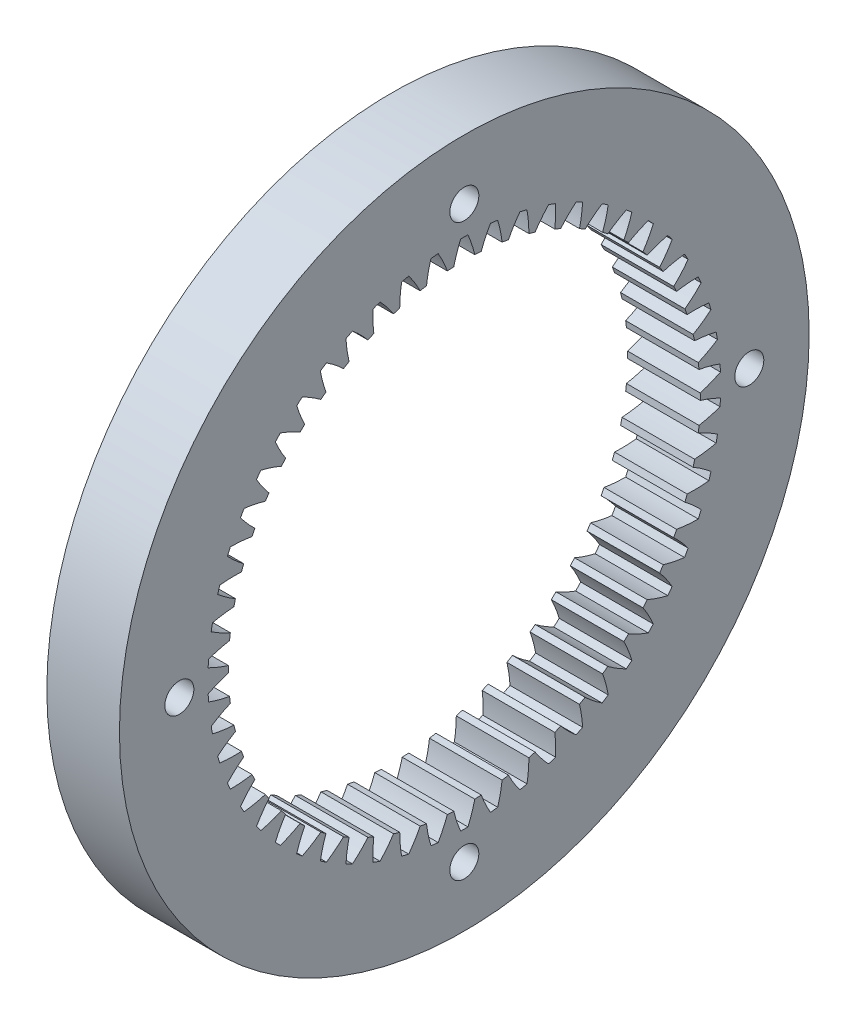
SolidWorks part; units mm, degrees
ref_plane "Plane1" through (0, 0, 0) normal (0, 0, 1) x (1, 0, 0)
ref_plane "Plane2" through (0, 0, 0) normal (0, 1, 0) x (1, 0, 0)
ref_plane "Plane3" through (0, 0, 0) normal (1, 0, 0) x (0, 0, -1)
sketch "HoldingSke" plane through (0, 0, 0) normal (0, 1, 0) x (1, 0, 0)
  line L0 (0, 0) -> (0.4702, -0.6472)
  line L1 (-15, 0) -> (100, 0) construction
  line L2 (0, 0) -> (-2.1039, 2.3779)
  line L3 (0, 0) -> (-11.863, 4.5341)
  line L4 (0, 0) -> (5.0761, 6.9867)
  line L5 (0, 0) -> (-23.7986, -8.8762)
  line L6 (0, 0) -> (-10.5278, -7.1032)
  line L7 (-2.1039, 2.3779) -> (3.3635, 27.1825)
  line L8 (-76.2, 3.6279) -> (-54.61, 3.6279)
  line L9 (-67.7845, 28.3722) -> (-49.3413, 33.142)
  line L10 (-76.2, 71.12) -> (104.1128, 71.12)
  line L11 (0, 0) -> (-10, 0)
  line L12 (-76.2, 101.6) -> (-76.155, 101.6)
  line L13 (24.9733, 27.94) -> (52.9518, 28.4284)
  line L14 (24.9733, 27.94) -> (24.9743, 27.94)
  line L15 (24.9733, 27.94) -> (100.4006, 29.5858)
  circle A0 centre (0, 0) radius 47.5
  circle A1 centre (0, 0) radius 12.7
  circle A2 centre (0, 0) radius 12.7
  dimension "MHD" = 25.4
  dimension "Hub_dia" = 25.4
  dimension "Diameter" = 95
  dimension "Num_teeth" = 54
  dimension "Pitch" = 0.8
  dimension "Overall_len" = 25.4
  dimension "Show_teeth" = 54
  dimension "Thickness" = 12.7
  dimension "OAL" = 25.4001
  dimension "T_dim" = 21.59
  dimension "Ap" = 14.5
  dimension "H" = 19.05
  dimension "Pitch_radius" = 180.3128
  dimension "Width" = 10
  dimension "Backlash" = 0.045
  dimension "Addendum_fac" = 1
  dimension "Dedendum_fac" = 1.25
  dimension "Clearance_fac" = 0.25
  dimension "Dedendum_add" = 0.001
  dimension "Module" = 1.25
sketch "BasProSke" plane through (0, 0, 0) normal (0, 1, 0) x (1, 0, 0)
  line L0 (-10, 0) -> (60, 0) construction
  line L1 (0, 32.5) -> (0, 47.5)
  line L2 (0, 32.5) -> (10, 32.5)
  line L3 (10, 32.5) -> (10, 47.5)
  line L4 (10, 47.5) -> (0, 47.5)
  dimension "Diameter" = 95
  dimension "Thickness" = 10
  dimension "Inside_diameter" = 65
revolve "Base-Revolve" add sketch "BasProSke" angle 360 about L0
sketch "TooCutSke" plane through (0, 0, 0) normal (1, 0, 0) x (0, 0, -1)
  line L3 (1.0941, 33.7323) -> (1.0941, 53.6633) construction
  line L4 (0, 0) -> (0, 59.563) construction
  line L5 (0, 0) -> (-3.9729, 68.2119) construction
  line L6 (-14.9767, 28.585) -> (36.0689, 31.5581) construction
  circle A0 centre (0, 0) radius 33.75 construction
  circle A1 centre (0, 0) radius 35.3135 construction
  circle A2 centre (0, 0) radius 29.4075 construction
  circle A3 centre (0, 0) radius 32.4746 construction
  arc A4 (1.4516, 32.4421) -> (0.5004, 35.31) centre (-14.9767, 28.585) ccw
  arc A5 (1.4516, 32.4421) -> (-1.4516, 32.4421) centre (0, 0) ccw
  arc A6 (0.5004, 35.31) -> (-0.5004, 35.31) centre (0, 0) ccw
  arc A7 (-0.5004, 35.31) -> (-1.4516, 32.4421) centre (14.9767, 28.585) ccw
  dimension "Pitch_dia" = 67.5
  dimension "Base_dia" = 58.815
  dimension "Root_dia" = 70.627
  dimension "Overcut_dia" = 64.9492
  dimension "Flank_rad" = 16.875
  dimension "Half_ang" = 3.333
  dimension "Half_CT" = 1.0941
extrude "ToothCut" cut sketch "TooCutSke" along normal through all
fillet "Breaks" [suppressed] radius 0.125
fillet "RootFillets" [suppressed] radius 0.3135
pattern_circular "TeethCuts" count 54 every 6.667 about axis through (-10, 0, 0) along (1, 0, 0) of "RootFillets", "Breaks", "ToothCut"
sketch "Sketch1" plane through (10, 0, 0) normal (1, 0, 0) x (0, 0, -1)
  circle A0 centre (0, 0) radius 39.25 construction
  circle A1 centre (0, 39.25) radius 2
  circle A2 centre (39.25, 0) radius 2
  circle A3 centre (0, -39.25) radius 2
  circle A4 centre (-39.25, 0) radius 2
  point P14 (0, 0)
  dimension "D1" = 78.5
  dimension "D2" = 4
  dimension "D3" = 4
extrude "Cut-Extrude1" cut sketch "Sketch1" against normal blind 10
equation "' \"Module@HoldingSke\" = 6.35"
equation "' \"Num_teeth@HoldingSke\" = 24"
equation "' \"Ap@HoldingSke\" =  14.5"
equation "' \"Ap@HoldingSke\" = 14.5"
equation "' \"Width@HoldingSke\" = 12"
equation "' \"Diameter@HoldingSke\" = 8 * 25.4"
equation "' \"Show_teeth@HoldingSke\" = 100"
equation "' \"Backlash@HoldingSke\" = 0.009 * 25.4"
equation "' \"Addendum_fac@HoldingSke\" = 1.0"
equation "' \"Dedendum_fac@HoldingSke\" = 1.25"
equation "' \"Dedendum_add@HoldingSke\" = 0.00005 * 25.4"
equation "' \"Clearance_fac@HoldingSke\" = 0.25"
equation "\"Pitch@HoldingSke\" = 1 / \"Module@HoldingSke\" "
equation "\"Overcut_dia@TooCutSke\" = (\"Num_teeth@HoldingSke\" - 2 * \"Addendum_fac@HoldingSke\") / \"Pitch@HoldingSke\" - 0.002 * 25.4"
equation "\"Pitch_dia@TooCutSke\" = \"Num_teeth@HoldingSke\" / \"Pitch@HoldingSke\""
equation "\"Base_dia@TooCutSke\" = \"Num_teeth@HoldingSke\" / \"Pitch@HoldingSke\" * cos((\"Ap@HoldingSke\"  * 3.14159265 / 180)) * 0.90"
equation "\"Root_dia@TooCutSke\" = \"Num_teeth@HoldingSke\"  / \"Pitch@HoldingSke\" + 2 *  \"Dedendum_fac@HoldingSke\"/ \"Pitch@HoldingSke\" + \"Dedendum_add@HoldingSke\" * 2"
equation "\"Half_ang@TooCutSke\" = 180 / \"Num_teeth@HoldingSke\""
equation "\"Half_CT@TooCutSke\" = \"Num_teeth@HoldingSke\" / \"Pitch@HoldingSke\" * sin((3.14159265 / 2 / \"Num_teeth@HoldingSke\")) / 2 + 10 * \"Backlash@HoldingSke\" / 4"
equation "\"Flank_rad@TooCutSke\" = \"Num_teeth@HoldingSke\" / \"Pitch@HoldingSke\" / 4"
equation "\"Radius@RootFillets\"= \"Clearance_fac@HoldingSke\" / \"Pitch@HoldingSke\" + \"Dedendum_add@HoldingSke\""
equation "\"Break_rad@Breaks\" = 0.02 / \"Pitch@HoldingSke\" * 5"
equation "\"Num_teeth@TeethCuts\" = int( \"Show_teeth@HoldingSke\" ) + 1"
equation "\"Num_teeth@TeethCuts\" = ((sgn( \"Num_teeth@TeethCuts\" - \"Num_teeth@HoldingSke\" )-1)*( \"Num_teeth@TeethCuts\" - \"Num_teeth@HoldingSke\" ))/-2+ \"Num_teeth@HoldingSke\""
equation "\"Num_teeth@TeethCuts\" = ((sgn( \"Num_teeth@TeethCuts\" - 2.0)+1)*( \"Num_teeth@TeethCuts\" - 2.0))/2 +2.0"
equation "\"Angle@TeethCuts\" = 360.0 / \"Num_teeth@HoldingSke\""
equation "\"Diameter@BasProSke\" = \"Num_teeth@HoldingSke\"  / \"Pitch@HoldingSke\" + 2 *  \"Dedendum_fac@HoldingSke\"/ \"Pitch@HoldingSke\" + \"Dedendum_add@HoldingSke\" * 2 + 0.002 * 25.4"
equation "\"Diameter@BasProSke\" = ((sgn( \"Diameter@BasProSke\"  - \"Diameter@HoldingSke\" )+1)*( \"Diameter@BasProSke\"  - \"Diameter@HoldingSke\" ))/2 + \"Diameter@HoldingSke\""
equation "\"Inside_diameter@BasProSke\" =  (\"Num_teeth@HoldingSke\" - 2 * \"Addendum_fac@HoldingSke\") / \"Pitch@HoldingSke\" "
equation "\"Thickness@BasProSke\"  = \"Width@HoldingSke\""
